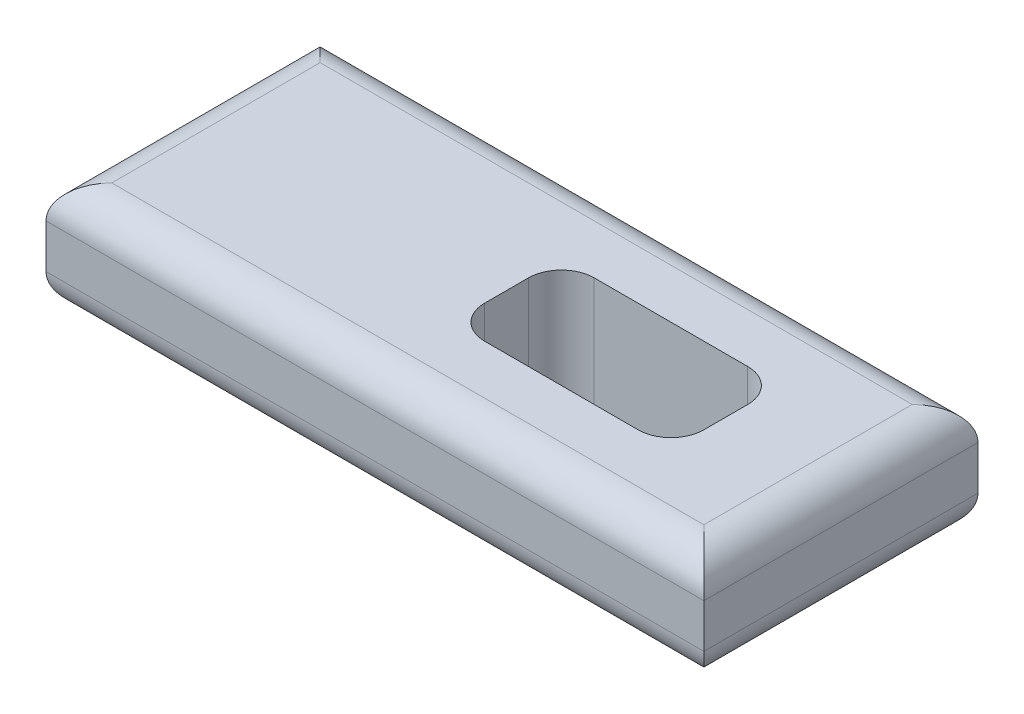
SolidWorks part; units mm, degrees
ref_plane "Plano frontal" through (0, 0, 0) normal (0, 0, 1) x (1, 0, 0)
ref_plane "Plano superior" through (0, 0, 0) normal (0, 1, 0) x (1, 0, 0)
ref_plane "Plano direito" through (0, 0, 0) normal (1, 0, 0) x (0, 0, -1)
sketch "Esboço2" plane through (0, 0, 0) normal (0, 1, 0) x (1, 0, 0)
  line L1 (0, 0) -> (120, 0)
  line L2 (0, 0) -> (0, 50)
  line L3 (0, 50) -> (120, 50)
  line L4 (120, 0) -> (120, 50)
  dimension "D1" = 120
  dimension "D2" = 50
extrude "Ressalto-extrusão1" add sketch "Esboço2" along normal blind 20
fillet "Filete1" radius 6 8 edges at (60, 0, -50) (0, 0, -25) (120, 0, -25) (60, 0, 0) (120, 20, -25) (0, 20, -25) (60, 20, -50) (60, 20, 0)
sketch "Esboço3" plane through (0, 20, 0) normal (0, 1, 0) x (1, 0, 0)
  line L0 (114, 44) -> (6, 44) construction
  line L1 (59, 35) -> (99, 35)
  line L2 (59, 35) -> (59, 15)
  line L3 (59, 15) -> (99, 15)
  line L4 (99, 35) -> (99, 15)
  line L7 (114, 6) -> (114, 44) construction
  dimension "D1" = 40
  dimension "D2" = 20
  dimension "D3" = 9
  dimension "D4" = 15
extrude "Corte-extrusão1" cut sketch "Esboço3" against normal through all
fillet "Filete2" radius 6 4 edges at (99, 10, -15) (59, 10, -15) (59, 10, -35) (99, 10, -35)
